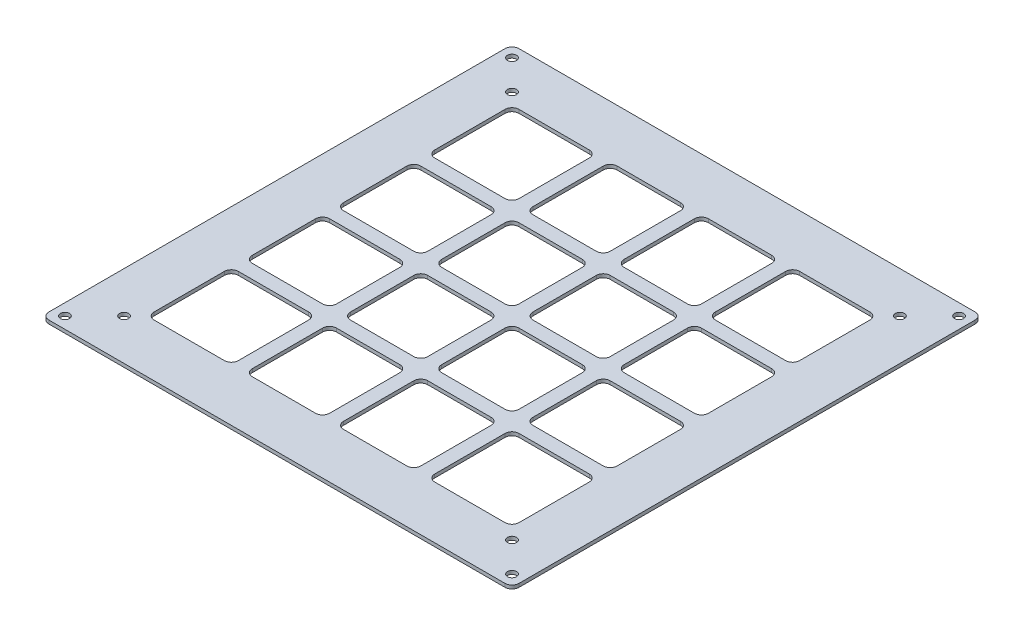
SolidWorks part; units mm, degrees
material "PC High Viscosity"
ref_plane "Front Plane" through (0, 0, 0) normal (0, 0, 1) x (1, 0, 0)
ref_plane "Top Plane" through (0, 0, 0) normal (0, 1, 0) x (1, 0, 0)
ref_plane "Right Plane" through (0, 0, 0) normal (1, 0, 0) x (0, 0, -1)
sketch "Sketch1" plane through (0, 0, 0) normal (0, 1, 0) x (1, 0, 0)
  line L0 (-101.8092, 0) -> (101.8092, 0) construction
  line L1 (-101.8092, 101.8092) -> (101.8092, 101.8092) construction
  line L2 (-101.8092, 101.8092) -> (-101.8092, -101.8092) construction
  line L3 (-101.8092, -101.8092) -> (101.8092, -101.8092) construction
  line L4 (101.8092, 101.8092) -> (101.8092, -101.8092) construction
  line L5 (-101.8092, 101.8092) -> (101.8092, -101.8092) construction
  line L6 (-101.8092, -101.8092) -> (101.8092, 101.8092) construction
  line L7 (-107.0543, 107.0543) -> (107.0543, 107.0543)
  line L8 (107.0543, 107.0543) -> (107.0543, -107.0543)
  line L9 (107.0543, -107.0543) -> (-107.0543, -107.0543)
  line L10 (-107.0543, -107.0543) -> (-107.0543, 107.0543)
  circle A0 centre (-101.8092, 101.8092) radius 2.0701
  circle A1 centre (-101.8092, -101.8092) radius 2.0701
  circle A2 centre (101.8092, -101.8092) radius 2.0701
  circle A3 centre (101.8092, 101.8092) radius 2.0701
  circle A4 centre (-88.3388, 88.3388) radius 2.0701
  circle A5 centre (88.3388, -88.3388) radius 2.0701
  circle A6 centre (88.3388, 88.3388) radius 2.0701
  circle A7 centre (-88.3388, -88.3388) radius 2.0701
  circle A8 centre (-101.8092, 101.8092) radius 5.2451 construction
  circle A9 centre (101.8092, 101.8092) radius 5.2451 construction
  circle A10 centre (101.8092, -101.8092) radius 5.2451 construction
  circle A11 centre (-101.8092, -101.8092) radius 5.2451 construction
  point P0 (0, 0)
  point P30 (0, 0)
  dimension "D2" = 4.1402
  dimension "D4" = 3.175
  dimension "D1" = 203.6183
  dimension "D3" = 19.05
  dimension "D5" = 4
extrude "Boss-Extrude1" add sketch "Sketch1" along normal blind 1.5875
sketch "Sketch2" plane through (0, 1.5875, 0) normal (0, 1, 0) x (1, 0, 0)
  line L0 (-50000, 0) -> (50000, 0) construction
  line L1 (0, 50000) -> (0, -50000) construction
  line L2 (0, 0) -> (-83.0937, 0) construction
  line L3 (0, 0) -> (0, 83.0937) construction
  line L4 (-83.0937, 83.0937) -> (-83.0937, -83.0937)
  line L5 (83.0937, 83.0937) -> (83.0937, -83.0937)
  line L6 (83.0937, -83.0937) -> (-83.0937, -83.0937)
  line L7 (-83.0937, 83.0937) -> (83.0937, 83.0937)
  line L8 (-41.5468, -83.0937) -> (-41.5468, 83.0937) construction
  line L9 (83.0937, 41.5468) -> (-83.0937, 41.5468) construction
  line L10 (83.0937, -41.5468) -> (-83.0937, -41.5468) construction
  line L11 (41.5468, -83.0937) -> (41.5468, 83.0937) construction
  line L12 (-83.0937, -3.175) -> (50000, -3.175)
  line L13 (-38.3718, -83.0937) -> (-38.3718, 83.0937)
  line L14 (83.0937, 44.7218) -> (-83.0937, 44.7218)
  line L15 (83.0937, -38.3718) -> (-83.0937, -38.3718)
  line L16 (-3.175, 83.0937) -> (-3.175, -83.0937)
  line L17 (44.7218, -83.0937) -> (44.7218, 83.0937)
  line L18 (-83.0937, 3.175) -> (50000, 3.175)
  line L19 (-44.7218, -83.0937) -> (-44.7218, 83.0937)
  line L20 (83.0937, 38.3718) -> (-83.0937, 38.3718)
  line L21 (83.0937, -44.7218) -> (-83.0937, -44.7218)
  line L22 (3.175, 83.0937) -> (3.175, -83.0937)
  line L23 (38.3718, -83.0937) -> (38.3718, 83.0937)
  line L24 (0, 44.7218) -> (-50000, 44.7218) construction
  line L25 (0, 41.5468) -> (-50000, 41.5468) construction
  line L26 (0, 38.3718) -> (-50000, 38.3718) construction
  line L27 (-50000, 3.175) -> (50000, 3.175) construction
  line L28 (-50000, -3.175) -> (50000, -3.175) construction
  line L29 (0, -38.3718) -> (-50000, -38.3718) construction
  line L30 (0, -41.5468) -> (-50000, -41.5468) construction
  line L31 (0, -44.7218) -> (-50000, -44.7218) construction
  line L32 (44.7218, 0) -> (44.7218, 50000) construction
  line L33 (41.5468, 0) -> (41.5468, 50000) construction
  line L34 (38.3718, 0) -> (38.3718, 50000) construction
  line L35 (-38.3718, 0) -> (-38.3718, 50000) construction
  line L36 (-41.5468, 0) -> (-41.5468, 50000) construction
  line L37 (-44.7218, 0) -> (-44.7218, 50000) construction
  line L38 (-3.175, 50000) -> (-3.175, -50000) construction
  line L39 (3.175, 50000) -> (3.175, -50000) construction
  circle A0 centre (-88.3388, 88.3388) radius 5.2451 construction
  circle A1 centre (-88.3388, 88.3388) radius 2.0701 construction
  circle A2 centre (88.3388, 88.3388) radius 5.2451 construction
  circle A3 centre (88.3388, -88.3388) radius 5.2451 construction
  circle A4 centre (-88.3388, -88.3388) radius 5.2451 construction
  point P19 (0, 0)
  point P22 (-41.5468, 0)
  point P27 (0, 41.5468)
  dimension "D1" = 3.175
  dimension "D3" = 3.175
  dimension "D4" = 3.175
  dimension "D2" = 4
extrude "Cut-Extrude1" cut sketch "Sketch2" against normal through all contours L14 L19 L7 L4 | L19 L20 L4 L18 | L16 L7 L13 L14 | L16 L20 L13 L18 | L14 L23 L7 L22 | L18 L23 L20 L22 | L17 L14 L5 L7 | L5 L20 L17 L18 | L17 L15 L5 L12 | L15 L23 L12 L22 | L16 L12 L13 L15 | L15 L19 L12 L4 | L19 L21 L4 L6 | L16 L21 L13 L6 | L6 L23 L21 L22 | L5 L21 L17 L6
fillet "Fillet1" radius 3.175 4 edges at (-107.0543, 0.7937, 107.0543) (107.0543, 0.7937, 107.0543) (107.0543, 0.7937, -107.0543) (-107.0543, 0.7937, -107.0543)
fillet "Fillet2" radius 3.175 64 edges at (-38.3718, 0.7937, -44.7218) (-38.3718, 0.7937, -83.0937) (-3.175, 0.7937, -83.0937) (-3.175, 0.7937, -44.7218) (-38.3718, 0.7937, -3.175) (-38.3718, 0.7937, -38.3718) (-3.175, 0.7937, -38.3718) (-3.175, 0.7937, -3.175) (3.175, 0.7937, -83.0937) (38.3718, 0.7937, -83.0937) (38.3718, 0.7937, -44.7218) (3.175, 0.7937, -44.7218) (83.0937, 0.7937, -83.0937) (83.0937, 0.7937, -44.7218) (44.7218, 0.7937, -44.7218) (44.7218, 0.7937, -83.0937) (44.7218, 0.7937, -3.175) (44.7218, 0.7937, -38.3718) (83.0937, 0.7937, -38.3718) (83.0937, 0.7937, -3.175) (83.0937, 0.7937, 3.175) (83.0937, 0.7937, 38.3718) (44.7218, 0.7937, 38.3718) (44.7218, 0.7937, 3.175) (3.175, 0.7937, 3.175) (38.3718, 0.7937, 3.175) (38.3718, 0.7937, 38.3718) (3.175, 0.7937, 38.3718) (-38.3718, 0.7937, 38.3718) (-38.3718, 0.7937, 3.175) (-3.175, 0.7937, 3.175) (-3.175, 0.7937, 38.3718) (-83.0937, 0.7937, 3.175) (-44.7218, 0.7937, 3.175) (-44.7218, 0.7937, 38.3718) (-83.0937, 0.7937, 38.3718) (-38.3718, 0.7937, 83.0937) (-38.3718, 0.7937, 44.7218) (-3.175, 0.7937, 44.7218) (-3.175, 0.7937, 83.0937) (3.175, 0.7937, 44.7218) (38.3718, 0.7937, 44.7218) (38.3718, 0.7937, 83.0937) (3.175, 0.7937, 83.0937) (44.7218, 0.7937, 83.0937) (44.7218, 0.7937, 44.7218) (83.0937, 0.7937, 44.7218) (83.0937, 0.7937, 83.0937) (-83.0937, 0.7937, -83.0937) (-44.7218, 0.7937, -83.0937) (-44.7218, 0.7937, -44.7218) (-83.0937, 0.7937, -44.7218) (-44.7218, 0.7937, 83.0937) (-83.0937, 0.7937, 44.7218) (-44.7218, 0.7937, 44.7218) (3.175, 0.7937, -3.175) (3.175, 0.7937, -38.3718) (38.3718, 0.7937, -38.3718) (38.3718, 0.7937, -3.175) (-44.7218, 0.7937, -3.175) (-83.0937, 0.7937, -3.175) (-83.0937, 0.7937, -38.3718) (-44.7218, 0.7937, -38.3718) (-83.0937, 0.7937, 83.0937)
